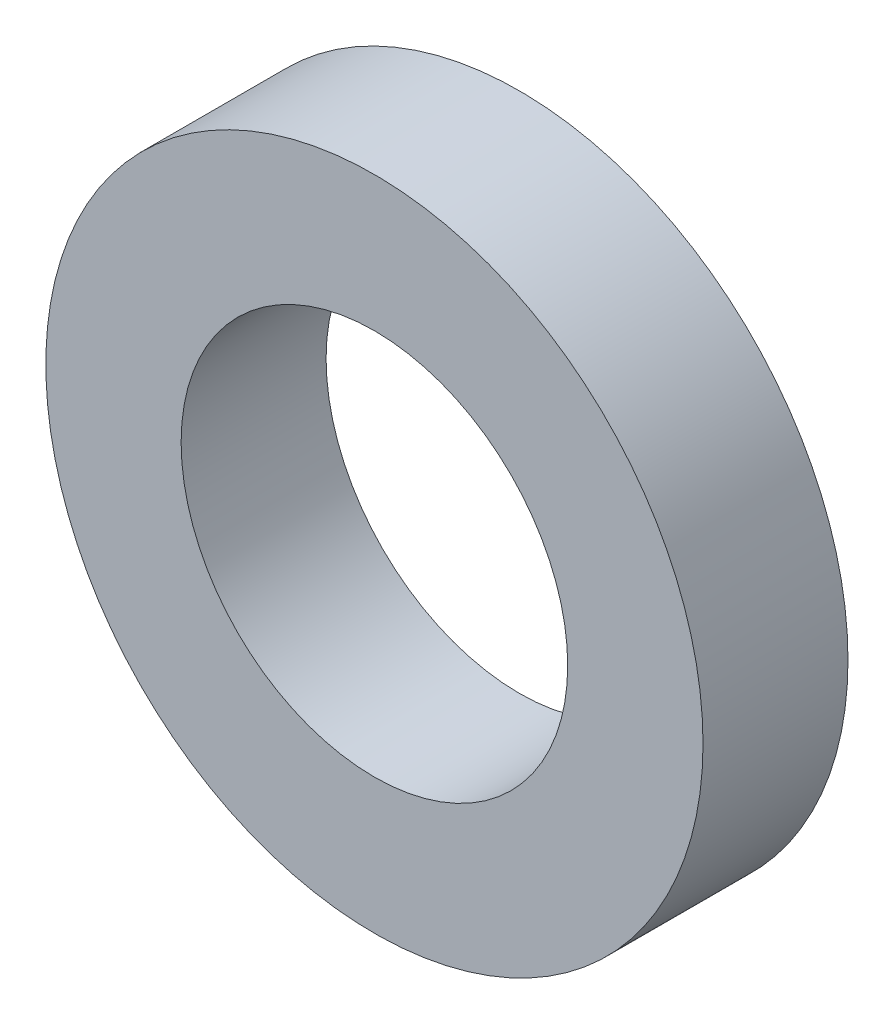
SolidWorks part; units mm, degrees
ref_plane "前视基准面" through (0, 0, 0) normal (0, 0, 1) x (1, 0, 0)
ref_plane "上视基准面" through (0, 0, 0) normal (0, 1, 0) x (1, 0, 0)
ref_plane "右视基准面" through (0, 0, 0) normal (1, 0, 0) x (0, 0, -1)
sketch "草图1" plane through (0, 0, 0) normal (0, 0, 1) x (1, 0, 0)
  circle A0 centre (0, 0) radius 34
  circle A1 centre (0, 0) radius 20
  dimension "D1" = 68
  dimension "D2" = 40
extrude "凸台-拉伸1" add sketch "草图1" along normal mid plane 15
